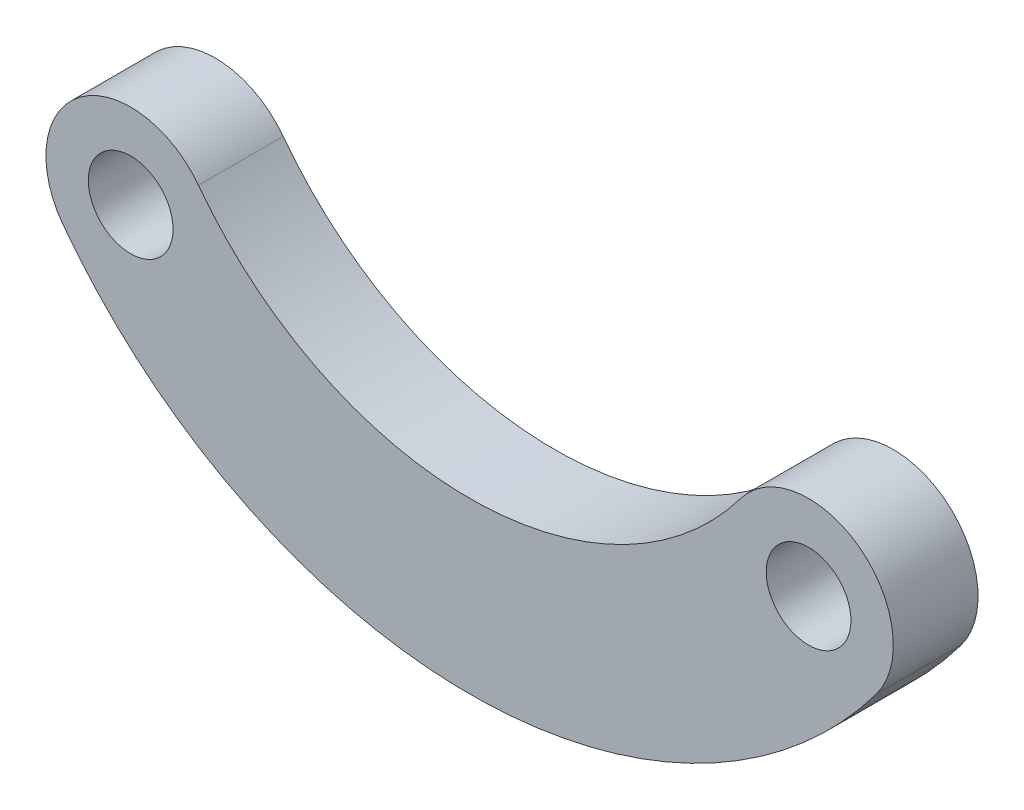
SolidWorks part; units mm, degrees
ref_plane "Front Plane" through (0, 0, 0) normal (0, 0, 1) x (1, 0, 0)
ref_plane "Top Plane" through (0, 0, 0) normal (0, 1, 0) x (1, 0, 0)
ref_plane "Right Plane" through (0, 0, 0) normal (1, 0, 0) x (0, 0, -1)
sketch "Sketch1" plane through (0, 0, 0) normal (0, 0, 1) x (1, 0, 0)
  line L0 (0, 0) -> (20.32, 0) construction
  circle A2 centre (0, 0) radius 1.27
  circle A3 centre (20.32, 0) radius 1.27
  arc A4 (0, 0) -> (20.32, 0) centre (10.16, 7.62) ccw construction
  arc A5 (-2.032, -1.524) -> (22.352, -1.524) centre (10.16, 7.62) ccw
  arc A6 (2.032, 1.524) -> (18.288, 1.524) centre (10.16, 7.62) ccw
  arc A7 (2.032, 1.524) -> (-2.032, -1.524) centre (0, 0) ccw
  arc A8 (22.352, -1.524) -> (18.288, 1.524) centre (20.32, 0) ccw
  point P13 (10.16, -5.08)
  dimension "D2" = 5.08
  dimension "D3" = 2.54
  dimension "D4" = 2.54
  dimension "D1" = 20.32
extrude "Boss-Extrude1" add sketch "Sketch1" along normal blind 2.54
